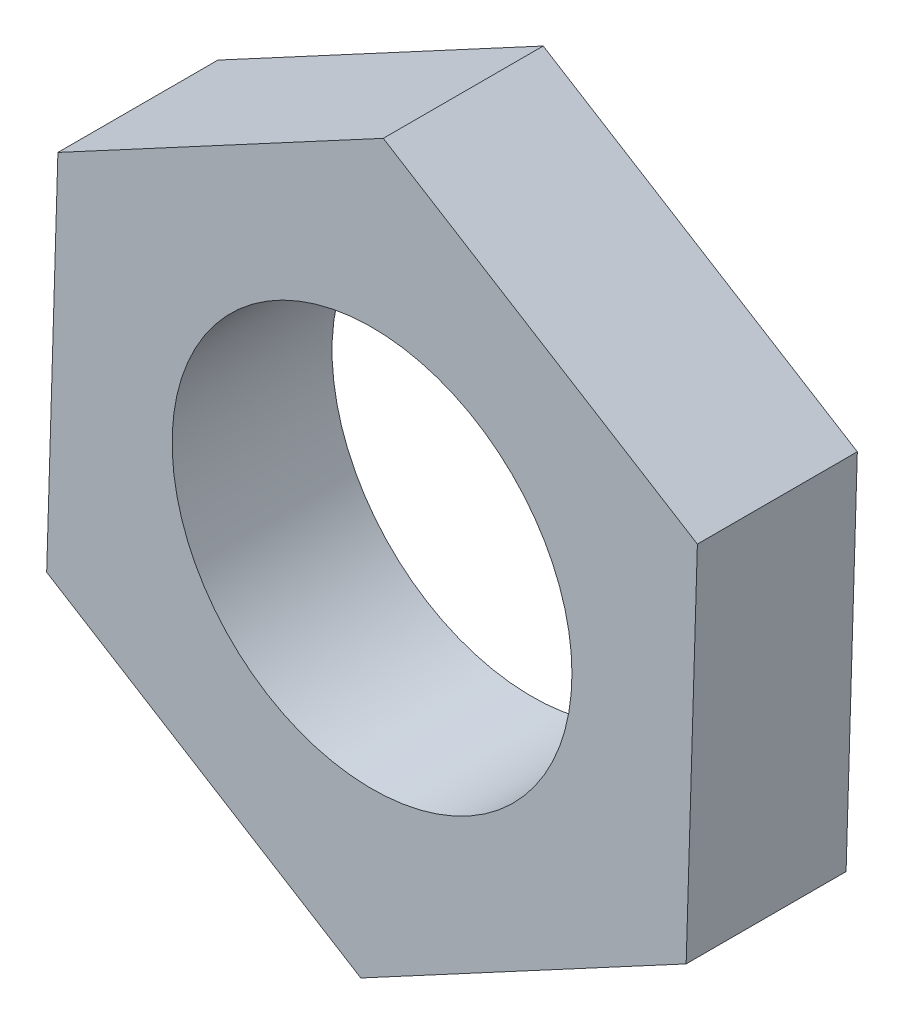
SolidWorks part; units mm, degrees
ref_plane "Front Plane" through (0, 0, 0) normal (0, 0, 1) x (1, 0, 0)
ref_plane "Top Plane" through (0, 0, 0) normal (0, 1, 0) x (1, 0, 0)
ref_plane "Right Plane" through (0, 0, 0) normal (1, 0, 0) x (0, 0, -1)
sketch "Sketch1" plane through (0, 0, 0) normal (0, 0, 1) x (1, 0, 0)
  line L1 (40.6835, 21.8674) -> (1.404, 46.1667)
  line L2 (1.404, 46.1667) -> (-39.2795, 24.2993)
  line L3 (-39.2795, 24.2993) -> (-40.6835, -21.8674)
  line L4 (-40.6835, -21.8674) -> (-1.404, -46.1667)
  line L5 (-1.404, -46.1667) -> (39.2795, -24.2993)
  line L6 (39.2795, -24.2993) -> (40.6835, 21.8674)
  circle A0 centre (0, 0) radius 40 construction
  circle A1 centre (0, 0) radius 25
  dimension "D1" = 80
  dimension "D2" = 50
extrude "Boss-Extrude1" add sketch "Sketch1" along normal blind 20
